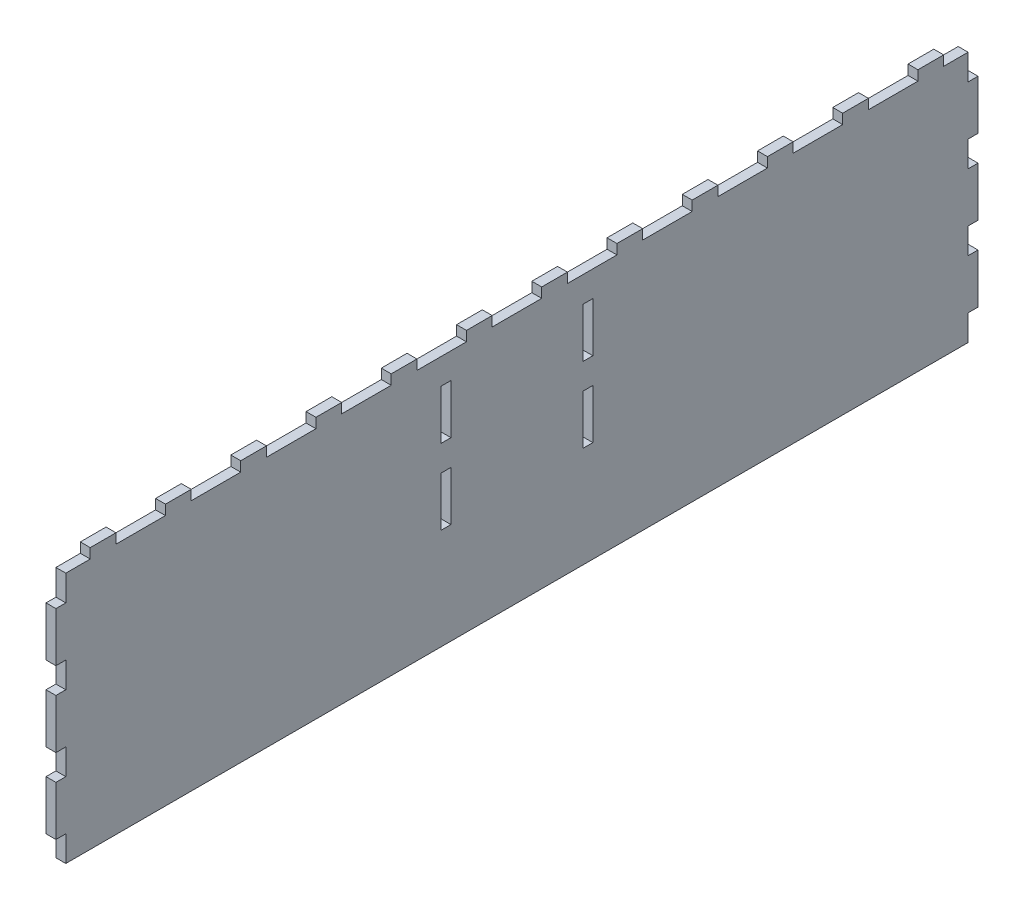
SolidWorks part; units mm, degrees
material "ENPH 253 Hardboard"
ref_plane "Front Plane" through (0, 0, 0) normal (0, 0, 1) x (1, 0, 0)
ref_plane "Top Plane" through (0, 0, 0) normal (0, 1, 0) x (1, 0, 0)
ref_plane "Right Plane" through (0, 0, 0) normal (1, 0, 0) x (0, 0, -1)
sketch "Sketch1" plane through (0, 0, 0) normal (1, 0, 0) x (0, 0, -1)
  line L1 (-139.7, 38.1) -> (139.7, 38.1)
  line L2 (-139.7, 38.1) -> (-139.7, -38.1)
  line L3 (-139.7, -38.1) -> (139.7, -38.1)
  line L4 (139.7, 38.1) -> (139.7, -38.1)
  line L5 (-139.7, 38.1) -> (139.7, -38.1) construction
  line L6 (-139.7, -38.1) -> (139.7, 38.1) construction
  point P0 (0, 0)
  dimension "D1" = 279.4
  dimension "D2" = 76.2
extrude "Boss-Extrude1" add sketch "Sketch1" against normal blind 3 contours L2 L3 L4 L1
sketch "Sketch3" plane through (-3, 0, 0) normal (-1, 0, 0) x (0, 0, 1)
  line L9 (-139.7, 38.1) -> (-136.7, 38.1)
  line L10 (-139.7, 38.1) -> (-139.7, 30.3)
  line L11 (-139.7, 30.3) -> (-136.7, 30.3)
  line L12 (-136.7, 38.1) -> (-136.7, 30.3)
  dimension "D9" = 7.8
  dimension "D10" = 3
extrude "Cut-Extrude1" cut sketch "Sketch3" against normal through all
pattern_linear "LPattern1" count 4 spacing 22.8 along (0, -1, 0) of "Cut-Extrude1"
mirror "Mirror1" about plane through (0, 0, 0) normal (0, 0, 1) of "LPattern1", "Cut-Extrude1"
sketch "Sketch5" plane through (-3, 0, 0) normal (-1, 0, 0) x (0, 0, 1)
  line L1 (-23, 30.3) -> (-20, 30.3)
  line L2 (-23, 30.3) -> (-23, 15.3)
  line L3 (-23, 15.3) -> (-20, 15.3)
  line L4 (-20, 30.3) -> (-20, 15.3)
  line L5 (136.7, 38.1) -> (-136.7, 38.1) construction
  line L6 (0, -1.65) -> (0, 1.65) construction
  dimension "D1" = 20
  dimension "D2" = 3
  dimension "D3" = 7.8
  dimension "D4" = 15
extrude "Cut-Extrude3" cut sketch "Sketch5" against normal blind 10
sketch "Sketch9" plane through (0, 38.1, 0) normal (0, 1, 0) x (1, 0, 0)
  line L0 (0, -136.7) -> (0, 136.7) construction
  line L1 (0, 129.3) -> (-3, 129.3)
  line L2 (0, 129.3) -> (0, 121.5)
  line L3 (0, 121.5) -> (-3, 121.5)
  line L4 (-3, 129.3) -> (-3, 121.5)
  line L5 (-3, -136.7) -> (-3, 136.7) construction
  line L6 (0, 136.7) -> (-3, 136.7) construction
  point P10 (-1.5, 129.3)
  dimension "D1" = 7.4
  dimension "D2" = 7.8
extrude "Boss-Extrude2" add sketch "Sketch9" along normal blind 3
pattern_linear "LPattern4" count 12 spacing 22.8 along (0, 0, 1) of "Boss-Extrude2"
pattern_linear "LPattern5" count 2 spacing 22.8 along (0, -1, 0) of "Cut-Extrude3"
mirror "Mirror2" about plane through (0, 0, 0) normal (0, 0, 1) of "LPattern5", "Cut-Extrude3"
